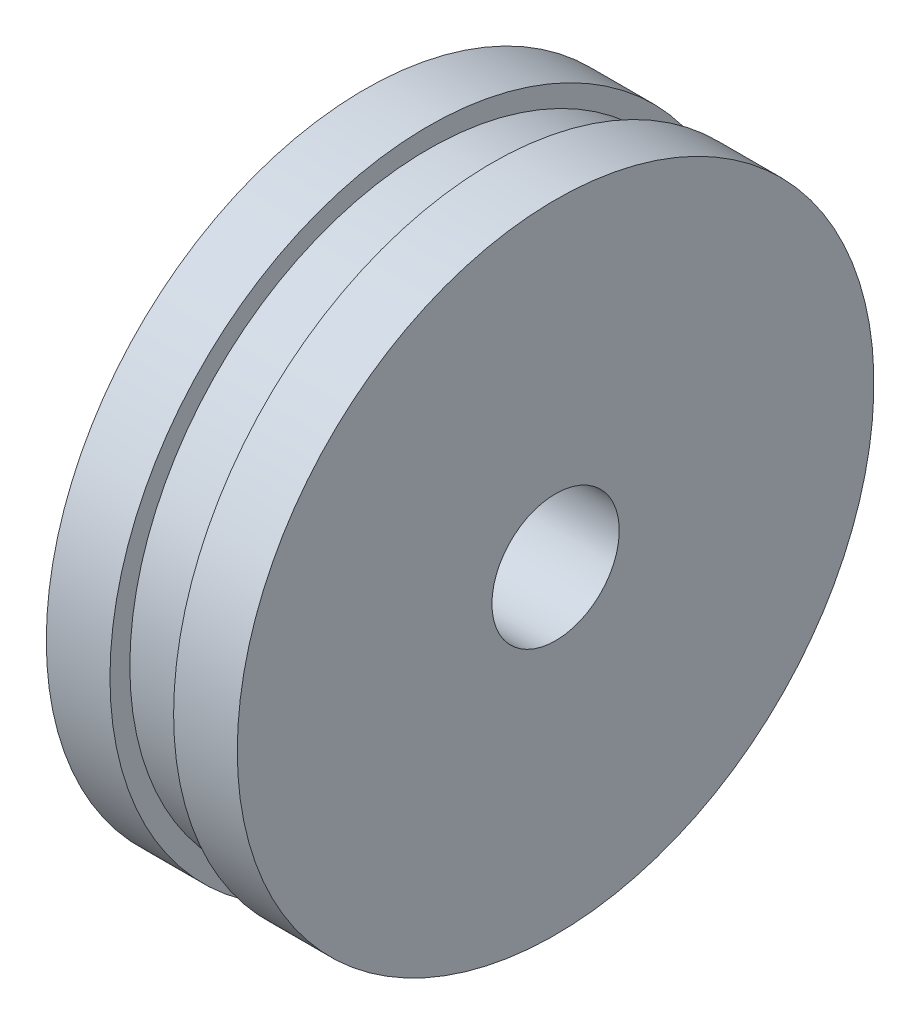
SolidWorks part; units mm, degrees
ref_plane "Front Plane" through (0, 0, 0) normal (0, 0, 1) x (1, 0, 0)
ref_plane "Top Plane" through (0, 0, 0) normal (0, 1, 0) x (1, 0, 0)
ref_plane "Right Plane" through (0, 0, 0) normal (1, 0, 0) x (0, 0, -1)
sketch "Sketch1" plane through (0, 0, 0) normal (0, 1, 0) x (1, 0, 0)
  line L0 (-28.819, 0) -> (28.274, 0) construction
  line L1 (0, 22.5851) -> (0, -16.7941) construction
  line L2 (6, 0) -> (-6, 0)
  line L3 (-6, 0) -> (-6, 20)
  line L4 (-6, 20) -> (-2, 20)
  line L5 (-2, 20) -> (-2, 18.75)
  line L6 (-2, 18.75) -> (2, 18.75)
  line L7 (2, 20) -> (2, 18.75)
  line L8 (6, 20) -> (2, 20)
  line L9 (6, 0) -> (6, 20)
  point P12 (0, 18.75)
  point P15 (0, 0)
  dimension "D1" = 6
  dimension "D2" = 2
  dimension "D3" = 18.75
  dimension "D4" = 20
revolve "Revolve1" add sketch "Sketch1" angle 360 about L0
sketch "Sketch2" plane through (-6, 0, 0) normal (-1, 0, 0) x (0, 0, 1)
  circle A0 centre (0, 0) radius 4
  dimension "D1" = 8
extrude "Cut-Extrude1" cut sketch "Sketch2" against normal blind 40
